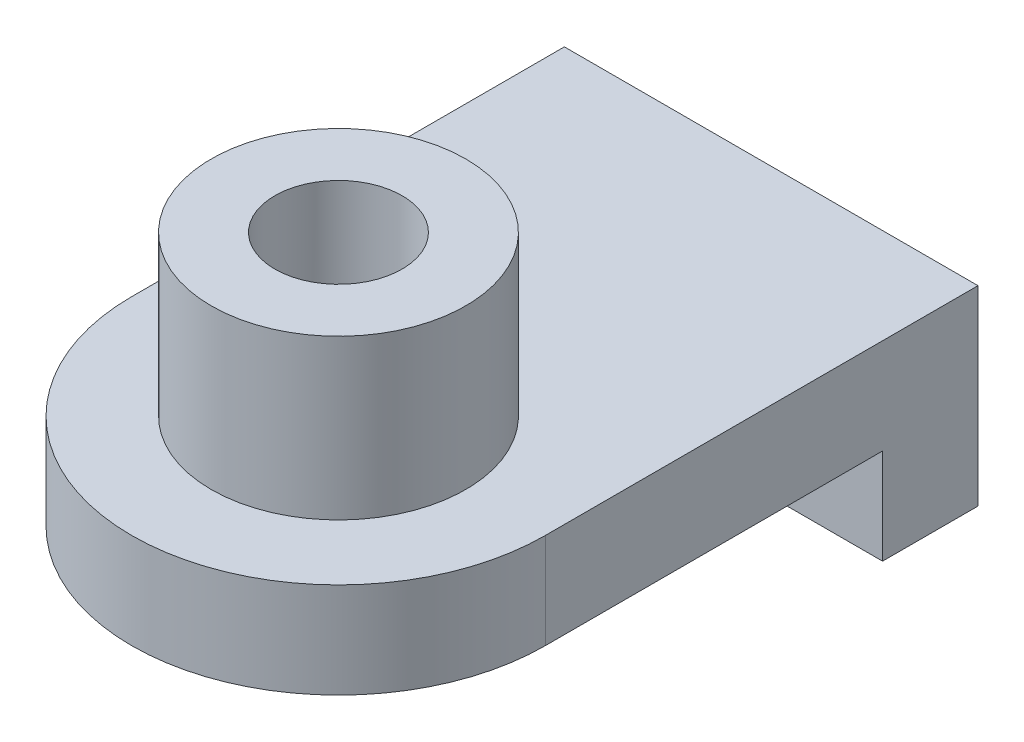
SolidWorks part; units mm, degrees
ref_plane "Front" through (0, 0, 0) normal (0, 0, 1) x (1, 0, 0)
ref_plane "Top" through (0, 0, 0) normal (0, 1, 0) x (1, 0, 0)
ref_plane "Right" through (0, 0, 0) normal (1, 0, 0) x (0, 0, -1)
sketch "Sketch1" plane through (0, 0, 0) normal (0, 1, 0) x (1, 0, 0)
  line L0 (32.5, 0) -> (32.5, 68)
  line L2 (-32.5, 68) -> (-32.5, 0)
  line L3 (-32.5, 68) -> (32.5, 68)
  arc A0 (32.5, 0) -> (-32.5, 0) centre (0, 0) cw
  dimension "D1" = 65
  dimension "D2" = 68
extrude "填料-伸長1" add sketch "Sketch1" along normal blind 15
sketch "Sketch2" plane through (32.5, 0, 0) normal (1, 0, 0) x (0, 0, -1)
  line L0 (68, 0) -> (53, 0)
  line L1 (68, 0) -> (68, -15)
  line L2 (53, -15) -> (68, -15)
  line L3 (53, -15) -> (53, 0)
  line L4 (0, 0) -> (68, 0) construction
  dimension "D1" = 15
  dimension "D2" = 15
extrude "填料-伸長2" add sketch "Sketch2" against normal through all
sketch "Sketch3" plane through (0, 15, 0) normal (0, 1, 0) x (-1, 0, 0)
  circle A0 centre (0, 0) radius 20
  dimension "D1" = 40
extrude "填料-伸長3" add sketch "Sketch3" along normal blind 25
hole_wizard "鑽孔1" positions "Sketch5" profile "Sketch4" legacy
sketch "Sketch5" plane through (0, 40, 0) normal (0, 1, 0) x (-1, 0, 0)
  circle A0 centre (0, 0) radius 20 construction
  point P0 (0, 0)
sketch "Sketch4" plane through (0, 40, 0) normal (1, 0, 0) x (0, 0, 1)
  line L0 (0, 0) -> (0, 25)
  line L1 (0, 25) -> (10, 25)
  line L2 (10, 25) -> (10, 0)
  line L3 (10, 0) -> (0, 0)
  line L4 (0, 110) -> (0, -10) construction
  dimension "Diameter" = 20
  dimension "Depth" = 25
